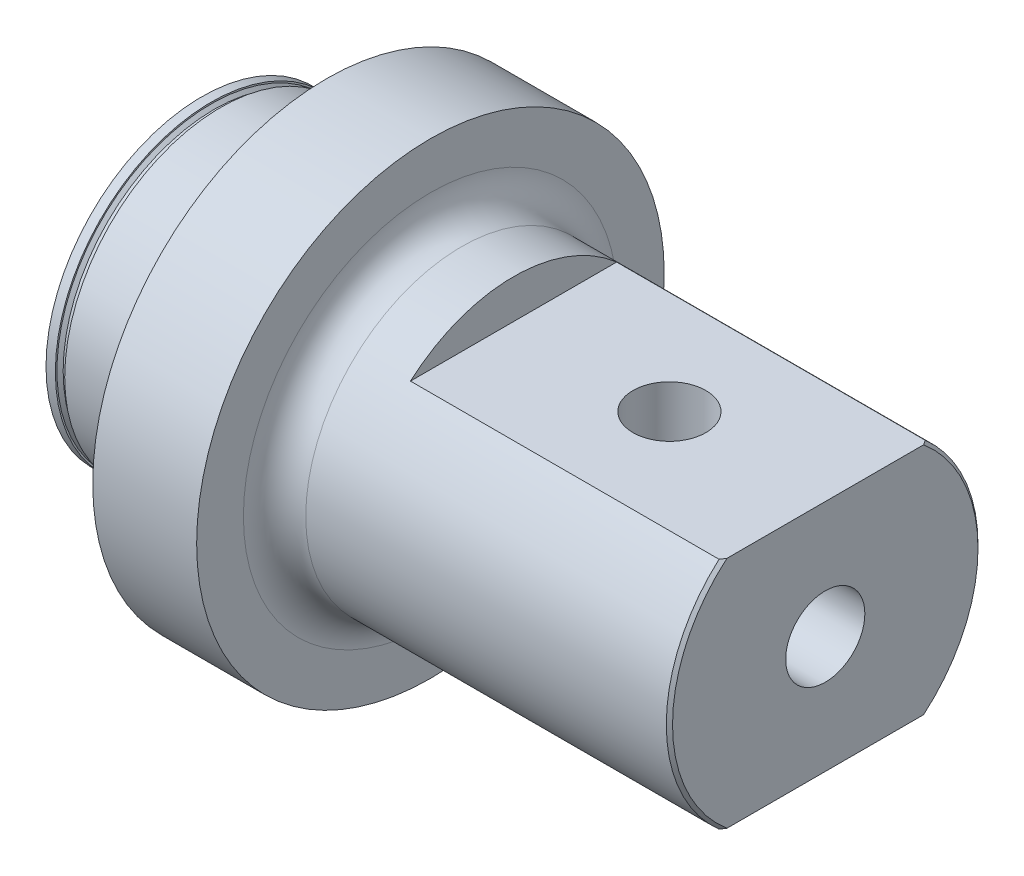
SolidWorks part; units mm, degrees
ref_plane "Front Plane" through (0, 0, 0) normal (0, 0, 1) x (1, 0, 0)
ref_plane "Top Plane" through (0, 0, 0) normal (0, 1, 0) x (1, 0, 0)
ref_plane "Right Plane" through (0, 0, 0) normal (1, 0, 0) x (0, 0, -1)
sketch "Sketch2" plane through (0, 0, 0) normal (0, 0, 1) x (1, 0, 0)
  line L0 (-100, 0) -> (100, 0)
  line L2 (-100, 50) -> (-100, -50)
  line L3 (-100, -50) -> (100, -50)
  line L4 (100, 50) -> (100, -50)
  line L5 (-100, 50) -> (100, -50) construction
  line L6 (-100, -50) -> (100, 50) construction
  line L7 (-60, 75) -> (-26.67, 75)
  line L8 (-60, 75) -> (-60, -75)
  line L9 (-60, -75) -> (-26.67, -75)
  line L10 (-26.67, 75) -> (-26.67, 60)
  line L11 (-60, 75) -> (-26.67, -75) construction
  line L12 (-60, -75) -> (-26.67, 75) construction
  line L13 (100, 50) -> (-16.67, 50)
  line L14 (-100, 50) -> (-60, 50)
  line L15 (-100, -50) -> (-97, -50) construction
  line L16 (-97, 48.5) -> (-97, 50)
  line L17 (-97, 48.5) -> (-94, 48.5)
  line L18 (-97, 48.5) -> (-97, -48.5)
  line L19 (-97, -48.5) -> (-94, -48.5)
  line L20 (-94, 48.5) -> (-94, -48.5)
  line L21 (-97, 48.5) -> (-94, -48.5) construction
  line L22 (-97, -48.5) -> (-94, 48.5) construction
  line L23 (-94, 48.5) -> (-94, 50)
  arc A0 (-26.67, 60) -> (-16.67, 50) centre (-16.67, 60) ccw
  point P0 (0, 0)
  point P6 (-43.335, 0)
  point P22 (-95.5, 0)
  dimension "D6" = 10
  dimension "D1" = 100
  dimension "D2" = 200
  dimension "D3" = 40
  dimension "D4" = 33.33
  dimension "D5" = 150
  dimension "D7" = 75
  dimension "D8" = 3
  dimension "D9" = 0
  dimension "D10" = 97
  dimension "D11" = 3
  dimension "D12" = 100
revolve "Revolve1" add sketch "Sketch2" angle 360 about L0
sketch "Sketch3" plane through (100, 0, 0) normal (1, 0, 0) x (0, 0, -1)
  line L0 (0, 37.5) -> (0, -37.5) construction
  line L1 (-33.0719, 37.5) -> (33.0719, 37.5)
  line L2 (-33.0719, -37.5) -> (33.0719, -37.5)
  circle A0 centre (0, 0) radius 50 construction
  circle A1 centre (0, 0) radius 50
  circle A2 centre (0, 0) radius 12.7
  point P7 (0, 0)
  point P9 (0, 37.5)
  point P12 (0, -37.5)
  circle M3 centre (0, 0) radius 50
  dimension "D2" = 25.4
  dimension "D1" = 75
extrude "Cut-Extrude1" cut sketch "Sketch3" against normal blind 100 contours L1 M3 | L2 M3
sketch "Sketch6" plane through (0, 37.5, 0) normal (0, 1, 0) x (1, 0, 0)
  line L0 (0, 33.0719) -> (100, 33.0719) construction
  point P0 (50, 0)
  point P6 (50, 33.0719)
hole_wizard "1-12 Tapped Hole1" positions "Sketch6" profile "Sketch7" tap size "1-12" standard "ANSI Inch" end condition through all
sketch "Sketch7" plane through (50, 37.5, 0) normal (1, 0, 0) x (0, 0, 1)
  line L0 (0, 0) -> (0, 112.5)
  line L1 (0, 112.5) -> (11.7081, 112.5)
  line L2 (11.7081, 112.5) -> (11.7081, 0)
  line L5 (11.7081, 0) -> (0, 0)
  line L11 (0, -6.35) -> (0, 107.95) construction
  dimension "Thru Tap Drill Dia." = 23.4163
  dimension "Thru Tap Drill Depth" = 112.5
sketch "Sketch8" plane through (100, 0, 0) normal (1, 0, 0) x (0, 0, -1)
  point P5 (0, 0)
  point P10 (0, 0)
hole_wizard "1 (1) Diameter Hole1" positions "Sketch8" profile "Sketch9" hole size "1" standard "ANSI Inch" end condition through all
sketch "Sketch9" plane through (100, 0, 0) normal (0, 1, 0) x (0, 0, -1)
  line L0 (0, 0) -> (0, 200)
  line L1 (0, 200) -> (12.7, 200)
  line L2 (12.7, 200) -> (12.7, 0)
  line L5 (12.7, 0) -> (0, 0)
  line L11 (0, -6.35) -> (0, 107.95) construction
  dimension "Thru Hole Dia." = 25.4
  dimension "Thru Hole Depth" = 200
chamfer "Chamfer1" distance 1 angle 45 3 edges at (-97, 0, 48.5) (100, 0, 50) (100, 0, -50)
equation "\"base\"=100"
equation "\"length\"=47.862"
equation "\"len\"= 200"
equation "\"D6@Sketch2\"=\"base\"/10"
equation "\"D2@Sketch2\"=\"len\""
